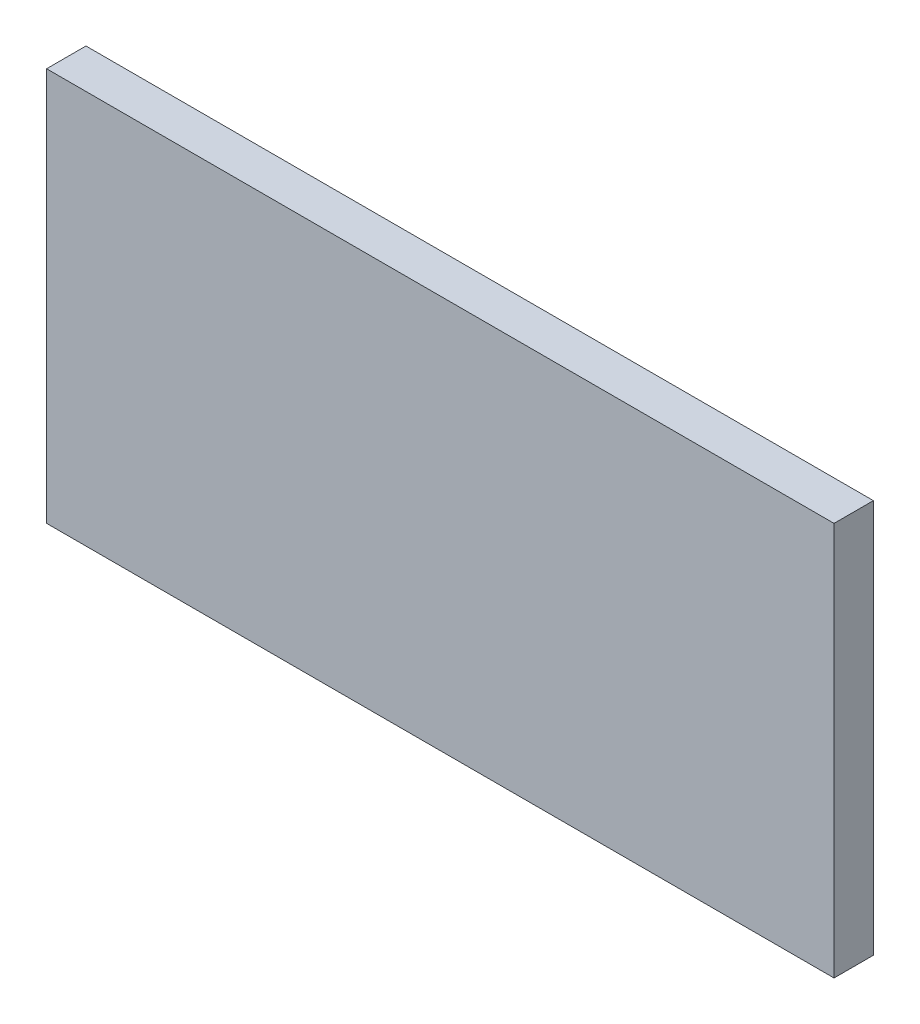
SolidWorks part; units mm, degrees
ref_plane "Plan de face" through (0, 0, 0) normal (0, 0, 1) x (1, 0, 0)
ref_plane "Plan de dessus" through (0, 0, 0) normal (0, 1, 0) x (1, 0, 0)
ref_plane "Plan de droite" through (0, 0, 0) normal (1, 0, 0) x (0, 0, -1)
sketch "Esquisse1" plane through (0, 0, 0) normal (0, 0, 1) x (1, 0, 0)
  line L1 (0, 0) -> (2000, 0)
  line L2 (0, 0) -> (0, 1000)
  line L3 (0, 1000) -> (2000, 1000)
  line L4 (2000, 0) -> (2000, 1000)
  dimension "D1" = 2000
  dimension "D2" = 1000
extrude "Boss.-Extru.1" add sketch "Esquisse1" along normal blind 100
